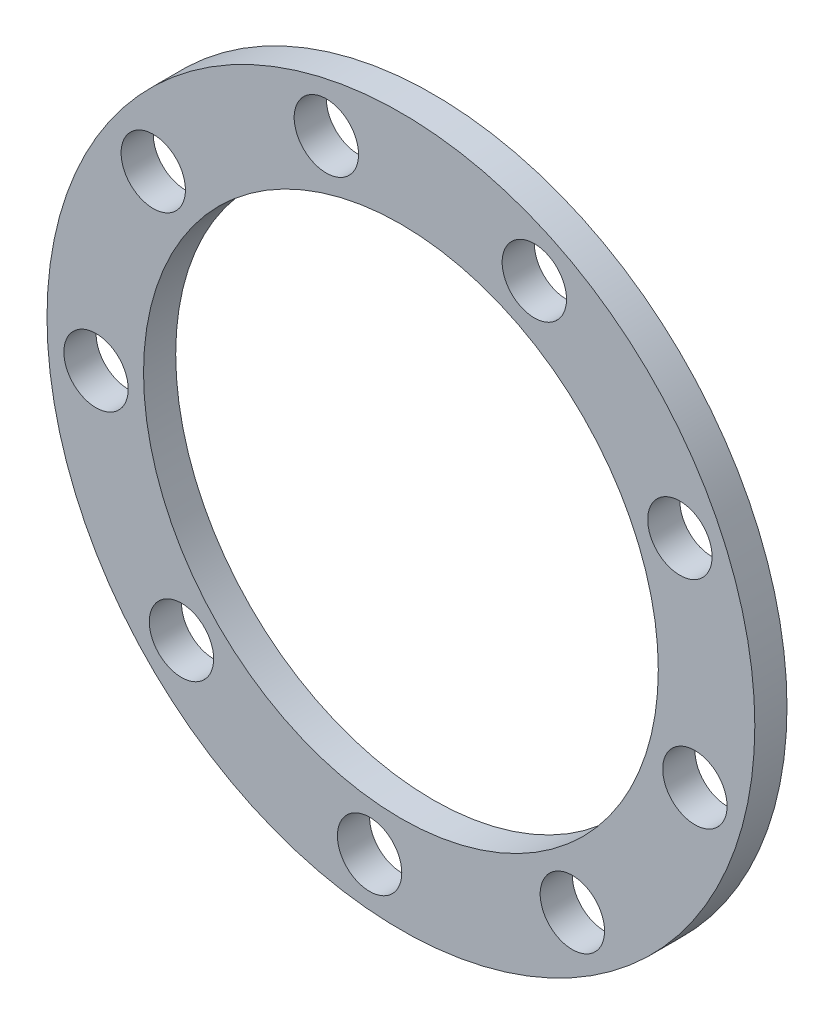
SolidWorks part; units mm, degrees
ref_plane "Front Plane" through (0, 0, 0) normal (0, 0, 1) x (1, 0, 0)
ref_plane "Top Plane" through (0, 0, 0) normal (0, 1, 0) x (1, 0, 0)
ref_plane "Right Plane" through (0, 0, 0) normal (1, 0, 0) x (0, 0, -1)
sketch "Sketch1" plane through (0, 0, 0) normal (0, 0, 1) x (1, 0, 0)
  line L0 (-2.6831, 10.6678) -> (-1.9513, 7.7584) construction
  circle A0 centre (0, 0) radius 8
  circle A1 centre (0, 0) radius 11
  circle A2 centre (-2.3172, 9.2131) radius 1
  circle A3 centre (4.147, 8.5471) radius 1
  circle A4 centre (8.6707, 3.8818) radius 1
  circle A5 centre (9.1373, -2.5998) radius 1
  circle A6 centre (5.3285, -7.8649) radius 1
  circle A7 centre (-0.9736, -9.45) radius 1
  circle A8 centre (-6.8201, -6.6133) radius 1
  circle A9 centre (-9.4755, -0.6822) radius 1
  circle A10 centre (-7.6971, 5.5682) radius 1
  point P26 (0, 0)
  point P28 (0, 0)
  dimension "D1" = 2
  dimension "D2" = 22
  dimension "D3" = 9
extrude "Boss-Extrude1" add sketch "Sketch1" along normal blind 1
